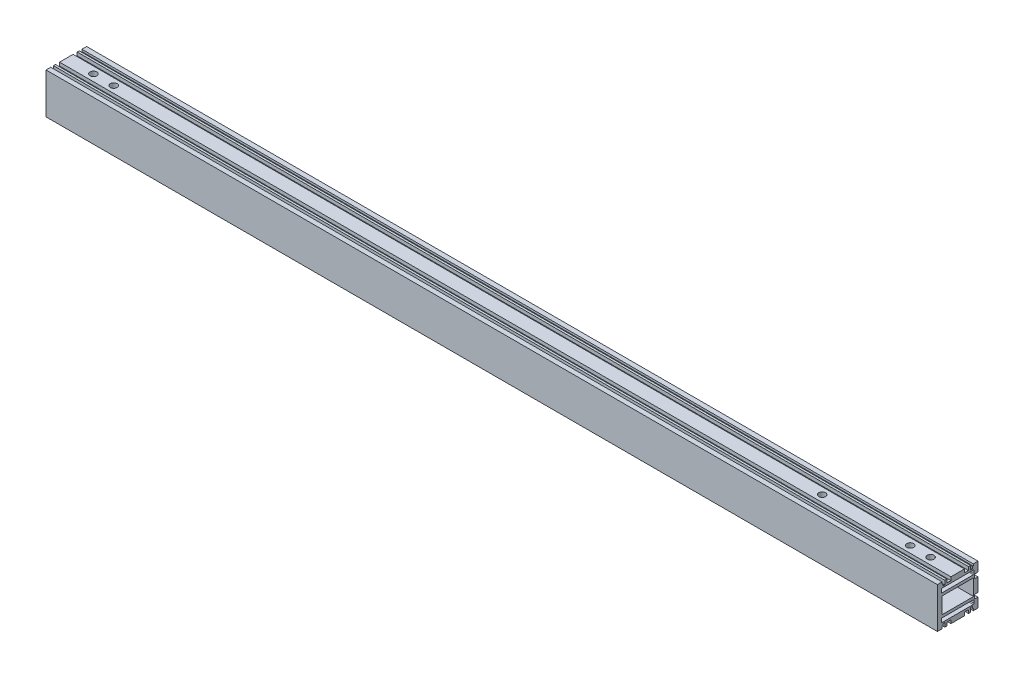
SolidWorks part; units mm, degrees
ref_plane "前视基准面" through (0, 0, 0) normal (0, 0, 1) x (1, 0, 0)
ref_plane "上视基准面" through (0, 0, 0) normal (0, 1, 0) x (1, 0, 0)
ref_plane "右视基准面" through (0, 0, 0) normal (1, 0, 0) x (0, 0, -1)
sketch "草图1" plane through (0, 0, 0) normal (1, 0, 0) x (0, 0, -1)
  line L0 (-15, 15) -> (15, -15) construction
  line L1 (-15, 15) -> (-11.5, 15)
  line L2 (-15, 15) -> (-15, -15)
  line L3 (-15, -15) -> (-11.5, -15)
  line L4 (15, 15) -> (15, 8)
  line L5 (15, 15) -> (-15, -15) construction
  line L6 (-11.5, 15) -> (-11.5, 13.5)
  line L7 (-11.5, 13.5) -> (-11, 13.5)
  line L8 (-11, 13.5) -> (-11, 12)
  line L9 (-11, 12) -> (-9.5, 12)
  line L10 (-9.5, 12) -> (-9.5, 15)
  line L11 (-9.5, 15) -> (-8, 15)
  line L12 (-8, 15) -> (-8, 12.5)
  line L13 (-8, 12.5) -> (-5, 12.5)
  line L14 (-5, 12.5) -> (-5, 15)
  line L15 (-5, 15) -> (5, 15)
  line L16 (0, 21.5201) -> (0, -18.309) construction
  line L17 (0, 55) -> (0, -55) construction
  line L18 (5, 12.5) -> (5, 15)
  line L19 (8, 12.5) -> (5, 12.5)
  line L20 (8, 15) -> (8, 12.5)
  line L21 (9.5, 15) -> (8, 15)
  line L22 (9.5, 12) -> (9.5, 15)
  line L23 (11, 12) -> (9.5, 12)
  line L24 (11, 13.5) -> (11, 12)
  line L25 (11.5, 13.5) -> (11, 13.5)
  line L26 (11.5, 15) -> (11.5, 13.5)
  line L27 (8, 15) -> (9.5, 15)
  line L28 (11.5, 15) -> (15, 15)
  line L29 (-19.8303, 0) -> (22.13, 0) construction
  line L30 (55, 0) -> (-55, 0) construction
  line L31 (8, -15) -> (9.5, -15)
  line L32 (11.5, -15) -> (11.5, -13.5)
  line L33 (11.5, -13.5) -> (11, -13.5)
  line L34 (11, -13.5) -> (11, -12)
  line L35 (11, -12) -> (9.5, -12)
  line L36 (9.5, -12) -> (9.5, -15)
  line L37 (9.5, -15) -> (8, -15)
  line L38 (8, -15) -> (8, -12.5)
  line L39 (8, -12.5) -> (5, -12.5)
  line L40 (5, -12.5) -> (5, -15)
  line L41 (-5, -15) -> (5, -15)
  line L42 (-5, -12.5) -> (-5, -15)
  line L43 (-8, -12.5) -> (-5, -12.5)
  line L44 (-8, -15) -> (-8, -12.5)
  line L45 (-9.5, -15) -> (-8, -15)
  line L46 (-9.5, -12) -> (-9.5, -15)
  line L47 (-11, -12) -> (-9.5, -12)
  line L48 (-11, -13.5) -> (-11, -12)
  line L49 (-11.5, -13.5) -> (-11, -13.5)
  line L50 (-11.5, -15) -> (-11.5, -13.5)
  line L51 (-9.5, -15) -> (-8, -15)
  line L52 (-5, -15) -> (5, -15)
  line L53 (8, -15) -> (9.5, -15)
  line L54 (11.5, -15) -> (15, -15)
  line L55 (15, 8) -> (12.5, 8)
  line L56 (12.5, 8) -> (12.5, 5)
  line L57 (12.5, 5) -> (15, 5)
  line L58 (12.5, -5) -> (15, -5)
  line L59 (12.5, -8) -> (12.5, -5)
  line L60 (15, -8) -> (12.5, -8)
  line L61 (15, 5) -> (15, -5)
  line L62 (15, -8) -> (15, -15)
  line L63 (12, -10.5) -> (12, -8.5)
  line L64 (-11.5, 11) -> (11.5, 11)
  line L65 (-12, 10.5) -> (-12, 8.5)
  line L66 (-11.5, 8) -> (11.5, 8)
  line L67 (12, 10.5) -> (12, 8.5)
  line L68 (-11.5, -8) -> (11.5, -8)
  line L69 (-12, -10.5) -> (-12, -8.5)
  line L70 (-11.5, -11) -> (11.5, -11)
  line L72 (-11.75, 6) -> (11.75, 6)
  line L73 (-11.75, 6) -> (-11.75, -6)
  line L74 (-11.75, -6) -> (11.75, -6)
  line L75 (11.75, 6) -> (11.75, -6)
  arc A0 (12, 8.5) -> (11.5, 8) centre (11.5, 8.5) cw
  arc A1 (11.5, 11) -> (12, 10.5) centre (11.5, 10.5) cw
  arc A2 (-11.5, 11) -> (-12, 10.5) centre (-11.5, 10.5) ccw
  arc A3 (-11.5, 8) -> (-12, 8.5) centre (-11.5, 8.5) cw
  arc A8 (-11.5, -8) -> (-12, -8.5) centre (-11.5, -8.5) ccw
  arc A9 (-11.5, -11) -> (-12, -10.5) centre (-11.5, -10.5) cw
  arc A10 (11.5, -11) -> (12, -10.5) centre (11.5, -10.5) ccw
  arc A11 (12, -8.5) -> (11.5, -8) centre (11.5, -8.5) ccw
  point P69 (12, 11)
  point P72 (-12, 11)
  point P77 (-11, -13.5)
  point P80 (11, -13.5)
  point P83 (11, 13.5)
  point P86 (-11, 13.5)
  point P99 (-12, -11)
  point P100 (12, -11)
  dimension "D17" = 0.5
  dimension "D1" = 3.5
  dimension "D2" = 1.5
  dimension "D3" = 0.5
  dimension "D4" = 1.5
  dimension "D5" = 3
  dimension "D6" = 30
  dimension "D7" = 30
  dimension "D8" = 1.5
  dimension "D9" = 2.5
  dimension "D10" = 3
  dimension "D11" = 2.5
  dimension "D12" = 7
  dimension "D13" = 3
  dimension "D14" = 4
  dimension "D15" = 3
  dimension "D16" = 24
  dimension "D19" = 23.5
  dimension "D20" = 12
extrude "凸台-拉伸1" add sketch "草图1" along normal mid plane 658
hole_wizard "M6 螺纹孔1" positions "草图3" profile "草图2" tap size "M6" standard "GB"
sketch "草图3" plane through (0, 15, 0) normal (0, 1, 0) x (1, 0, 0)
  line L0 (329, 15) -> (-329, 15) construction
  line L1 (329, 11.5) -> (329, 15) construction
  point P0 (-309, 0)
  point P3 (-294, 0)
  point P6 (294, 0)
  point P9 (309, 0)
  point P12 (229, 0)
  dimension "D1" = 15
  dimension "D2" = 100
sketch "草图2" plane through (-309, 15, 0) normal (1, 0, 0) x (0, 0, 1)
  line L0 (0, 0) -> (0, 20.5022)
  line L1 (0, 20.5022) -> (2.5, 19)
  line L2 (2.5, 19) -> (2.5, 0)
  line L5 (2.5, 0) -> (0, 0)
  line L10 (0, 20.5022) -> (-2.5, 19) construction
  line L11 (0, -6.35) -> (0, 107.95) construction
  dimension "螺纹孔钻头直径" = 5
  dimension "螺纹孔钻头深度" = 19
  dimension "导头角度" = 118
cosmetic thread "孔螺蚊线1" parameters "D1"=9, "D2"=6
cosmetic thread "孔螺蚊线2" parameters "D1"=9, "D2"=6
cosmetic thread "孔螺蚊线3" parameters "D1"=9, "D2"=6
cosmetic thread "孔螺蚊线4" parameters "D1"=9, "D2"=6
cosmetic thread "孔螺蚊线9" parameters "D1"=9, "D2"=6
hole_wizard "M6 螺纹孔2" positions "草图5" profile "草图4" tap size "M6" standard "GB"
sketch "草图5" plane through (0, -15, 0) normal (0, -1, 0) x (-1, 0, 0)
  point P0 (-309, 0)
  point P3 (-294, 0)
  point P6 (309, 0)
  point P9 (294, 0)
sketch "草图4" plane through (309, -15, 0) normal (1, 0, 0) x (0, 0, -1)
  line L0 (0, 0) -> (0, 20.5022)
  line L1 (0, 20.5022) -> (2.5, 19)
  line L2 (2.5, 19) -> (2.5, 0)
  line L5 (2.5, 0) -> (0, 0)
  line L10 (0, 20.5022) -> (-2.5, 19) construction
  line L11 (0, -6.35) -> (0, 107.95) construction
  dimension "螺纹孔钻头直径" = 5
  dimension "螺纹孔钻头深度" = 19
  dimension "导头角度" = 118
cosmetic thread "孔螺蚊线5" parameters "D1"=9, "D2"=6
cosmetic thread "孔螺蚊线6" parameters "D1"=9, "D2"=6
cosmetic thread "孔螺蚊线7" parameters "D1"=9, "D2"=6
cosmetic thread "孔螺蚊线8" parameters "D1"=9, "D2"=6
hole_wizard "M6 螺纹孔3" positions "草图7" profile "草图6" tap size "M6" standard "GB"
sketch "草图7" plane through (0, 0, -15) normal (0, 0, -1) x (-1, 0, 0)
  line L0 (-329, -15) -> (329, -15) construction
  line L1 (329, 5) -> (329, -5) construction
  line L2 (-329, -15) -> (329, -15) construction
  point P0 (194, 0)
  point P2 (89, 0)
  point P4 (29, 0)
  point P6 (-76, 0)
  dimension "D1" = 15
  dimension "D2" = 135
  dimension "D3" = 15
  dimension "D4" = 240
  dimension "D5" = 15
  dimension "D6" = 300
  dimension "D7" = 405
  dimension "D8" = 15
sketch "草图6" plane through (-194, 0, -15) normal (1, 0, 0) x (0, 1, 0)
  line L0 (0, 0) -> (0, 20.5022)
  line L1 (0, 20.5022) -> (2.5, 19)
  line L2 (2.5, 19) -> (2.5, 0)
  line L5 (2.5, 0) -> (0, 0)
  line L10 (0, 20.5022) -> (-2.5, 19) construction
  line L11 (0, -6.35) -> (0, 107.95) construction
  dimension "螺纹孔钻头直径" = 5
  dimension "螺纹孔钻头深度" = 19
  dimension "导头角度" = 118
cosmetic thread "孔螺蚊线10" parameters "D1"=3.25, "D2"=6
cosmetic thread "孔螺蚊线11" parameters "D1"=3.25, "D2"=6
cosmetic thread "孔螺蚊线12" parameters "D1"=3.25, "D2"=6
cosmetic thread "孔螺蚊线13" parameters "D1"=3.25, "D2"=6
